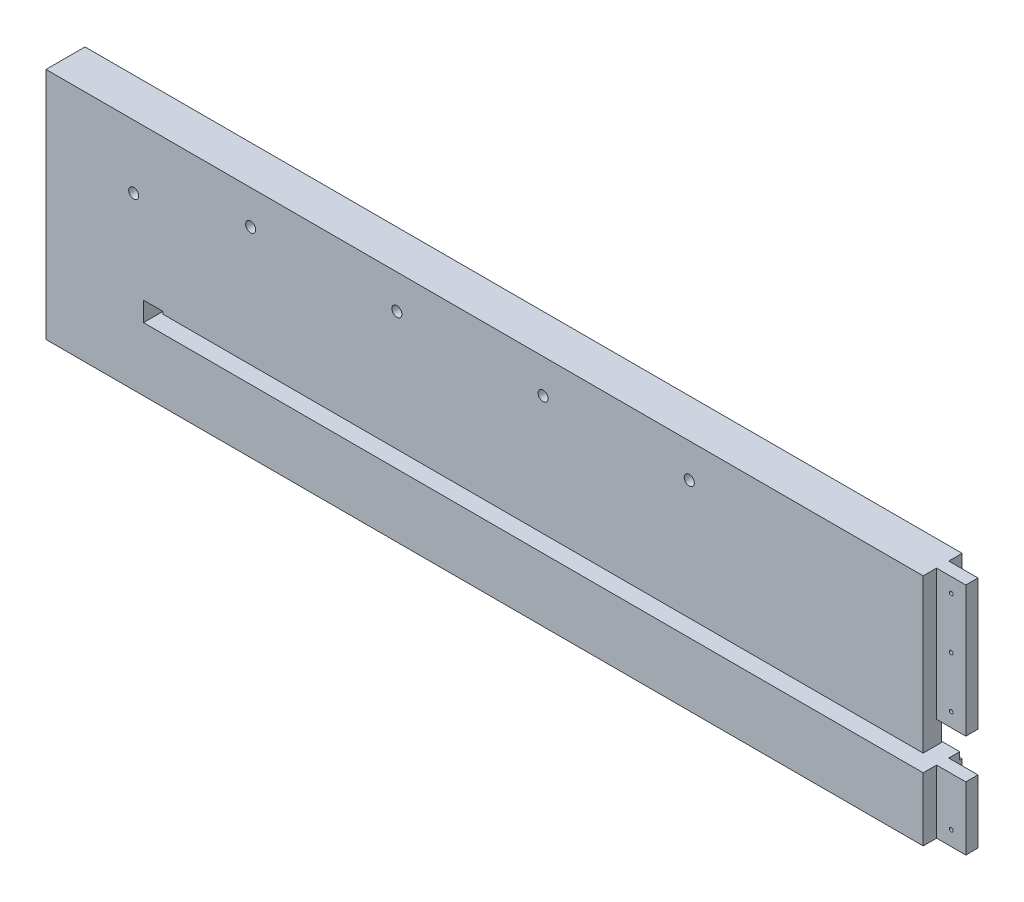
SolidWorks part; units mm, degrees
material "Pine"
ref_plane "Front Plane" through (0, 0, 0) normal (0, 0, 1) x (1, 0, 0)
ref_plane "Top Plane" through (0, 0, 0) normal (0, 1, 0) x (1, 0, 0)
ref_plane "Right Plane" through (0, 0, 0) normal (1, 0, 0) x (0, 0, -1)
sketch "Sketch1" plane through (0, 0, 0) normal (0, 0, 1) x (1, 0, 0)
  line L1 (1181.1, 304.8) -> (-1181.1, 304.8)
  line L2 (1181.1, 304.8) -> (1181.1, -304.8)
  line L3 (1181.1, -304.8) -> (-1181.1, -304.8)
  line L4 (-1181.1, 304.8) -> (-1181.1, -304.8)
  line L5 (1181.1, 304.8) -> (-1181.1, -304.8) construction
  line L6 (1181.1, -304.8) -> (-1181.1, 304.8) construction
  line L7 (-927.1, -88.9) -> (-876.3, -88.9)
  line L8 (-927.1, -88.9) -> (-927.1, -139.7)
  line L9 (-927.1, -139.7) -> (-876.3, -139.7)
  line L10 (-876.3, -88.9) -> (-876.3, -139.7)
  line L11 (-927.1, -88.9) -> (-876.3, -139.7) construction
  line L12 (-927.1, -139.7) -> (-876.3, -88.9) construction
  circle A0 centre (-952.5, 139.7) radius 13.1198
  circle A1 centre (-647.7, 215.9) radius 13.1198
  circle A2 centre (-266.7, 215.9) radius 13.1198
  circle A3 centre (114.3, 215.9) radius 13.1198
  circle A4 centre (495.3, 215.9) radius 13.1198
  point P0 (0, 0)
  point P10 (-901.7, -114.3)
  dimension "D10" = 381
  dimension "D11" = 381
  dimension "D12" = 381
  dimension "D1" = 609.6
  dimension "D2" = 2362.2
  dimension "D3" = 88.9
  dimension "D4" = 228.6
  dimension "D5" = 304.8
  dimension "D6" = 165.1
  dimension "D7" = 165.1
  dimension "D8" = 50.8
  dimension "D9" = 254
extrude "Boss-Extrude1" add sketch "Sketch1" along normal blind 101.6
sketch "Sketch2" plane through (0, 0, 0) normal (0, 0, -1) x (-1, 0, 0)
  line L0 (1181.1, -304.8) -> (-1181.1, -304.8) construction
  line L1 (673.1, -288.925) -> (-749.3, -288.925)
  line L2 (673.1, -288.925) -> (673.1, -273.05)
  line L3 (673.1, -273.05) -> (-749.3, -273.05)
  line L4 (-749.3, -288.925) -> (-749.3, -273.05)
  line L5 (673.1, -288.925) -> (-749.3, -273.05) construction
  line L6 (673.1, -273.05) -> (-749.3, -288.925) construction
  line L7 (1181.1, 304.8) -> (1181.1, -304.8) construction
  line L9 (673.1, -273.05) -> (800.1, -273.05)
  line L10 (673.1, -273.05) -> (673.1, -209.55)
  line L11 (673.1, -209.55) -> (800.1, -209.55)
  line L12 (800.1, -273.05) -> (800.1, -209.55)
  line L13 (673.1, -273.05) -> (800.1, -209.55) construction
  line L14 (673.1, -209.55) -> (800.1, -273.05) construction
  line L15 (800.1, 209.55) -> (673.1, 209.55)
  line L16 (800.1, 209.55) -> (800.1, 273.05)
  line L17 (800.1, 273.05) -> (673.1, 273.05)
  line L18 (673.1, 209.55) -> (673.1, 273.05)
  line L19 (800.1, 209.55) -> (673.1, 273.05) construction
  line L20 (800.1, 273.05) -> (673.1, 209.55) construction
  line L21 (-876.3, -273.05) -> (-749.3, -273.05)
  line L22 (-876.3, -273.05) -> (-876.3, -209.55)
  line L23 (-876.3, -209.55) -> (-749.3, -209.55)
  line L24 (-749.3, -273.05) -> (-749.3, -209.55)
  line L25 (-876.3, -273.05) -> (-749.3, -209.55) construction
  line L26 (-876.3, -209.55) -> (-749.3, -273.05) construction
  line L27 (-749.3, 209.55) -> (-876.3, 209.55)
  line L28 (-749.3, 209.55) -> (-749.3, 273.05)
  line L29 (-749.3, 273.05) -> (-876.3, 273.05)
  line L30 (-876.3, 209.55) -> (-876.3, 273.05)
  line L31 (-749.3, 209.55) -> (-876.3, 273.05) construction
  line L32 (-749.3, 273.05) -> (-876.3, 209.55) construction
  point P0 (-38.1, -280.9875)
  point P9 (736.6, -241.3)
  point P14 (736.6, 241.3)
  point P19 (-812.8, -241.3)
  point P24 (-812.8, 241.3)
  point P29 (673.1, -241.3)
  dimension "D1" = 15.875
  dimension "D2" = 15.875
  dimension "D3" = 508
  dimension "D4" = 1422.4
  dimension "D5" = 95.25
  dimension "D6" = 508
  dimension "D7" = 15.875
  dimension "D8" = 419.1
  dimension "D9" = 15.875
  dimension "D10" = 127
  dimension "D11" = 63.5
  dimension "D12" = 127
  dimension "D13" = 63.5
  dimension "D14" = 63.5
  dimension "D15" = 127
extrude "Cut-Extrude1" cut sketch "Sketch2" against normal blind 50.8 contours L18 L15 L16 L17 | L9 L12 L11 L10 | L30 L27 L28 L29 | L21 L24 L23 L22
sketch "Sketch3" plane through (0, -304.8, 0) normal (0, -1, 0) x (1, 0, 0)
  line L0 (749.3, 0) -> (876.3, 0) construction
  line L1 (876.3, 0) -> (876.3, 50.8) construction
  line L2 (876.3, 50.8) -> (749.3, 50.8) construction
  line L3 (749.3, 50.8) -> (749.3, 0) construction
  line L4 (-800.1, 0) -> (-673.1, 0) construction
  line L5 (-673.1, 0) -> (-673.1, 50.8) construction
  line L6 (-673.1, 50.8) -> (-800.1, 50.8) construction
  line L7 (-800.1, 50.8) -> (-800.1, 0) construction
  line L8 (749.3, 0) -> (876.3, 0)
  line L9 (876.3, 0) -> (876.3, 50.8)
  line L10 (876.3, 50.8) -> (749.3, 50.8)
  line L11 (749.3, 50.8) -> (749.3, 0)
  line L12 (-800.1, 0) -> (-673.1, 0)
  line L13 (-673.1, 0) -> (-673.1, 50.8)
  line L14 (-673.1, 50.8) -> (-800.1, 50.8)
  line L15 (-800.1, 50.8) -> (-800.1, 0)
  line L16 (-800.1, 25.4) -> (-673.1, 25.4) construction
  line L17 (749.3, 25.4) -> (876.3, 25.4) construction
  circle A0 centre (-704.85, 25.4) radius 4.7625
  circle A1 centre (-768.35, 25.4) radius 4.7625
  circle A2 centre (781.05, 25.4) radius 4.7625
  circle A3 centre (844.55, 25.4) radius 4.7625
  point P14 (-736.6, 25.4)
  point P21 (812.8, 25.4)
  dimension "D1" = 9.525
  dimension "D4" = 9.525
  dimension "D2" = 31.75
  dimension "D3" = 31.75
  dimension "D5" = 31.75
  dimension "D6" = 31.75
extrude "Cut-Extrude2" cut sketch "Sketch3" against normal blind 152.4 contours A3 | A2 | A0 | A1
sketch "Sketch4" plane through (0, -304.8, 0) normal (0, -1, 0) x (1, 0, 0)
  line L0 (1104.9, 101.6) -> (1104.9, 0)
  line L1 (-1181.1, 101.6) -> (1181.1, 101.6) construction
  line L2 (-1181.1, 0) -> (1181.1, 0) construction
  line L3 (1181.1, 101.6) -> (1181.1, 0) construction
  line L4 (1104.9, 50.8) -> (1181.1, 50.8) construction
  line L5 (1104.9, 101.6) -> (1181.1, 101.6)
  line L6 (1104.9, 66.675) -> (1181.1, 66.675)
  line L7 (1104.9, 66.675) -> (1104.9, 34.925)
  line L8 (1104.9, 34.925) -> (1181.1, 34.925)
  line L9 (1181.1, 66.675) -> (1181.1, 34.925)
  line L10 (1104.9, 66.675) -> (1181.1, 34.925) construction
  line L11 (1104.9, 34.925) -> (1181.1, 66.675) construction
  line L12 (1181.1, 101.6) -> (1181.1, 66.675)
  line L13 (1104.9, 0) -> (1181.1, 0)
  line L14 (1181.1, 0) -> (1181.1, 34.925)
  point P10 (1143, 50.8)
  line M8 (-1181.1, 0) -> (1181.1, 0)
  line M9 (1181.1, 0) -> (1181.1, 101.6)
  line M10 (1181.1, 101.6) -> (-1181.1, 101.6)
  dimension "D1" = 76.2
  dimension "D2" = 31.75
extrude "Cut-Extrude3" cut sketch "Sketch4" against normal through all contours L8 L0 M8 M9 | L0 L6 M9 M10
sketch "Sketch5" plane through (1181.1, 0, 0) normal (1, 0, 0) x (0, 0, -1)
  line L0 (0, -158.75) -> (-6.35, -158.75) construction
  line L1 (-6.35, -158.75) -> (-6.35, -139.7) construction
  line L2 (0, -139.7) -> (-6.35, -139.7) construction
  line L3 (0, -17.4625) -> (-6.35, -17.4625) construction
  line L4 (0, -36.5125) -> (-6.35, -36.5125) construction
  line L5 (-6.35, -36.5125) -> (-6.35, -17.4625) construction
  line L6 (0, -158.75) -> (-6.35, -158.75)
  line L7 (-6.35, -158.75) -> (-6.35, -139.7)
  line L8 (0, -139.7) -> (-6.35, -139.7)
  line L9 (0, -17.4625) -> (-6.35, -17.4625)
  line L10 (0, -36.5125) -> (-6.35, -36.5125)
  line L11 (-6.35, -36.5125) -> (-6.35, -17.4625)
  line L12 (-31.75, -77.7875) -> (-101.6, -77.7875) construction
  line L13 (-101.6, 304.8) -> (-101.6, -304.8) construction
  line L14 (-101.6, -95.25) -> (-53.975, -95.25)
  line L15 (-53.975, -95.25) -> (-53.975, -36.5125)
  line L16 (-53.975, -36.5125) -> (-6.35, -36.5125)
  line L17 (-101.6, -95.25) -> (-101.6, -139.7)
  line L18 (0, -139.7) -> (0, -36.5125)
  line L19 (-101.6, -139.7) -> (-6.35, -139.7)
  line L20 (0, -17.4625) -> (0, -36.5125)
  line L21 (0, -139.7) -> (0, -158.75)
  circle A0 centre (-31.75, -77.7875) radius 19.05 construction
  circle A1 centre (-31.75, -77.7875) radius 19.05
  point P16 (-3.175, -139.7)
  dimension "D1" = 44.45
  dimension "D2" = 47.625
  dimension "D3" = 58.7375
extrude "Cut-Extrude4" cut sketch "Sketch5" against normal blind 352.425 and the other way through all
sketch "Sketch6" plane through (1181.1, 0, 0) normal (1, 0, 0) x (0, 0, -1)
  line L0 (0, -158.75) -> (0, -17.4625) construction
  line L1 (-101.6, -139.7) -> (0, -139.7)
  line L2 (-101.6, -139.7) -> (-101.6, -36.5125)
  line L3 (-101.6, -36.5125) -> (0, -36.5125)
  line L4 (0, -139.7) -> (0, -36.5125)
  line L5 (-101.6, -139.7) -> (0, -36.5125) construction
  line L6 (-101.6, -36.5125) -> (0, -139.7) construction
  line L7 (-101.6, 304.8) -> (-101.6, -95.25) construction
  line L8 (-34.925, -36.5125) -> (-53.975, -36.5125) construction
  line L9 (-66.675, -139.7) -> (-34.925, -139.7) construction
  point P0 (-50.8, -88.1063)
extrude "Cut-Extrude5" cut sketch "Sketch6" against normal up to surface (76.2 mm away) up to face at (1104.9, 104.775, 84.1375)
sketch "Sketch7" plane through (0, 0, 66.675) normal (0, 0, 1) x (1, 0, 0)
  circle A0 centre (1143, 266.7) radius 4.7625 construction
  circle A1 centre (1143, 133.35) radius 4.7625 construction
  circle A2 centre (1143, 0) radius 4.7625 construction
  circle A3 centre (1143, -266.7) radius 4.7625 construction
  circle A4 centre (1143, 266.7) radius 4.7625
  circle A5 centre (1143, 133.35) radius 4.7625
  circle A6 centre (1143, 0) radius 4.7625
  circle A7 centre (1143, -266.7) radius 4.7625
extrude "Cut-Extrude6" cut sketch "Sketch7" against normal through all
sketch "Sketch9" plane through (0, 0, 101.6) normal (0, 0, 1) x (1, 0, 0)
  line L1 (828.675, -95.25) -> (-876.3, -95.25)
  line L2 (828.675, -95.25) -> (828.675, -139.7)
  line L3 (828.675, -139.7) -> (-876.3, -139.7)
  line L4 (-876.3, -95.25) -> (-876.3, -139.7)
extrude "Cut-Extrude7" cut sketch "Sketch9" against normal through all
